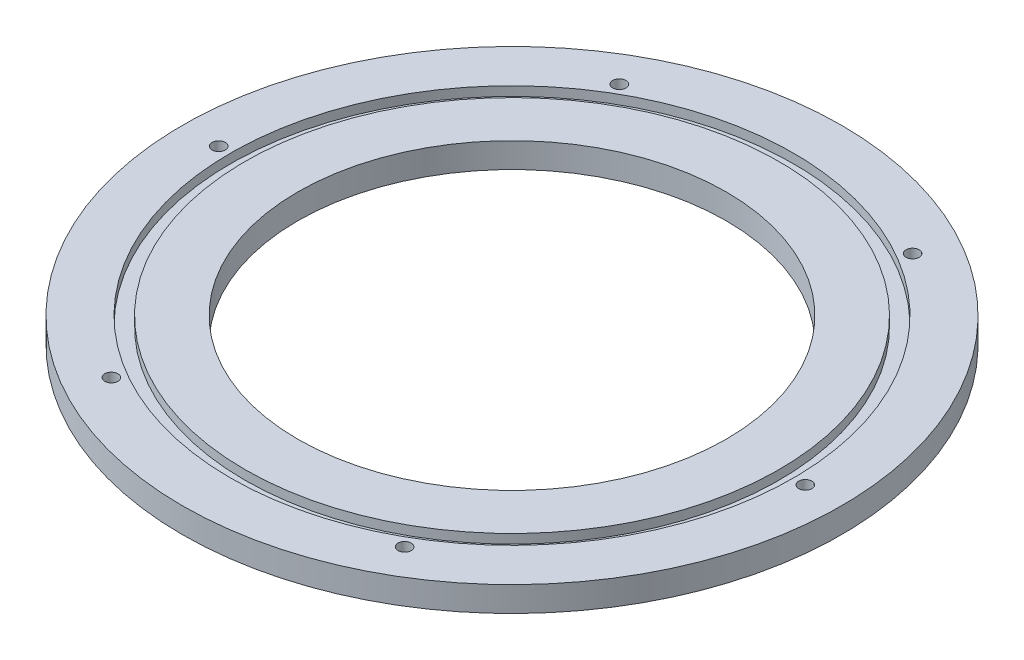
SolidWorks part; units mm, degrees
material "Pine"
ref_plane "Front Plane" through (0, 0, 0) normal (0, 0, 1) x (1, 0, 0)
ref_plane "Top Plane" through (0, 0, 0) normal (0, 1, 0) x (1, 0, 0)
ref_plane "Right Plane" through (0, 0, 0) normal (1, 0, 0) x (0, 0, -1)
sketch "Sketch1" plane through (0, 0, 0) normal (0, 1, 0) x (1, 0, 0)
  circle A0 centre (0, 0) radius 250
  circle A2 centre (0, 0) radius 162.5
  dimension "D1" = 500
  dimension "D2" = 325
extrude "Boss-Extrude1" add sketch "Sketch1" along normal mid plane 19
sketch "Sketch2" plane through (0, 9.5, 0) normal (0, 1, 0) x (1, 0, 0)
  circle A0 centre (0, 0) radius 202.5
  circle A1 centre (0, 0) radius 213.5
  dimension "D1" = 405
  dimension "D2" = 427
extrude "Cut-Extrude1" cut sketch "Sketch2" against normal blind 7
sketch "Sketch3" plane through (0, -9.5, 0) normal (0, -1, 0) x (1, 0, 0)
  line L0 (-1000, 0) -> (49000, 0) construction
  line L1 (0, -1000) -> (0, 49000) construction
  line L2 (-500, -866.0254) -> (24500, 42435.2448) construction
  line L3 (-500, 866.0254) -> (24500, -42435.2448) construction
  circle A0 centre (111.25, 192.6907) radius 5
  circle A1 centre (222.5, 0) radius 5
  circle A2 centre (-222.5, 0) radius 5
  circle A3 centre (-111.25, 192.6907) radius 5
  circle A4 centre (-111.25, -192.6907) radius 5
  circle A5 centre (111.25, -192.6907) radius 5
  dimension "D1" = 10
  dimension "D2" = 10
  dimension "D3" = 222.5
  dimension "D4" = 222.5
extrude "Cut-Extrude2" cut sketch "Sketch3" against normal through all
